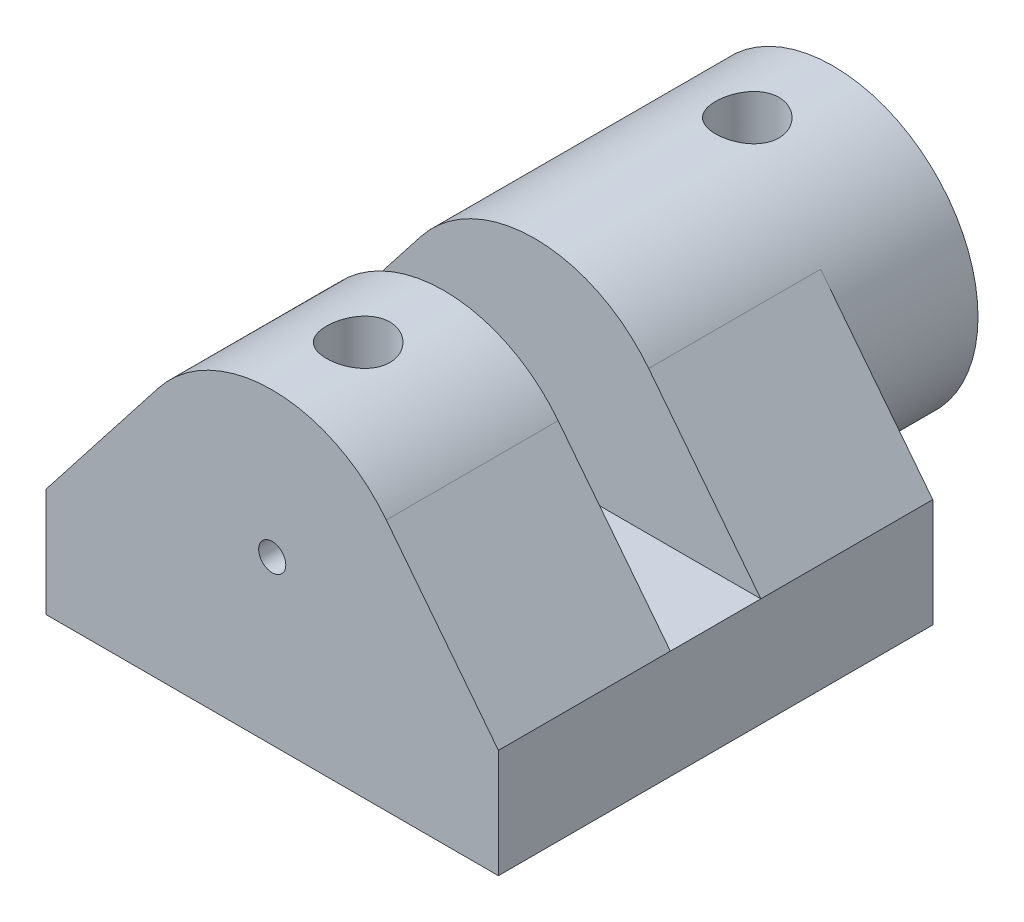
SolidWorks part; units mm, degrees
ref_plane "Front Plane" through (0, 0, 0) normal (0, 0, 1) x (1, 0, 0)
ref_plane "Top Plane" through (0, 0, 0) normal (0, 1, 0) x (1, 0, 0)
ref_plane "Right Plane" through (0, 0, 0) normal (1, 0, 0) x (0, 0, -1)
sketch "Sketch1" plane through (0, 0, 0) normal (0, 0, 1) x (1, 0, 0)
  line L0 (-12.5, 0) -> (12.5, 0)
  line L1 (12.5, 0) -> (12.5, 6)
  line L2 (12.5, 6) -> (6.3025, 13.9273)
  line L3 (-6.3025, 13.9273) -> (-12.5, 6)
  line L4 (-12.5, 6) -> (-12.5, 0)
  arc A0 (6.3025, 13.9273) -> (-6.3025, 13.9273) centre (0, 9) ccw
  circle A1 centre (0, 9) radius 0.75
  point P0 (0, 0)
  dimension "D2" = 8
  dimension "D5" = 1.5
  dimension "D3" = 25
  dimension "D1" = 6
  dimension "D4" = 3
extrude "Boss-Extrude1" add sketch "Sketch1" along normal blind 24
sketch "Sketch2" plane through (0, 0, 0) normal (0, 0, -1) x (-1, 0, 0)
  circle A1 centre (0, 9) radius 2.65
  circle A2 centre (0, 9) radius 8
  arc A3 (6.3025, 13.9273) -> (-6.3025, 13.9273) centre (0, 9) ccw construction
  circle A4 centre (0, 9) radius 0.75 construction
  dimension "D1" = 5.3
extrude "Boss-Extrude2" add sketch "Sketch2" along normal blind 7
sketch "Sketch4" plane through (12.5, 0, 0) normal (1, 0, 0) x (0, 0, -1)
  line L0 (-24, 6) -> (0, 6) construction
  line L1 (-14.5, 6) -> (-9.5, 6)
  line L2 (-14.5, 6) -> (-14.5, 17)
  line L3 (-14.5, 17) -> (-9.5, 17)
  line L4 (-9.5, 6) -> (-9.5, 17)
  line L5 (7, 17) -> (-24, 17) construction
  point P8 (-12, 6)
  point P9 (-12, 6)
  dimension "D1" = 5
extrude "Cut-Extrude1" cut sketch "Sketch4" against normal through all
sketch "Sketch5" plane through (0, 0, 0) normal (0, -1, 0) x (1, 0, 0)
  line L0 (-6.3025, 14.5) -> (6.3025, 14.5) construction
  line L1 (-6.3025, 14.5) -> (6.3025, 14.5) construction
  line L2 (0, 14.5) -> (0, 24) construction
  line L3 (-12.5, 24) -> (12.5, 24) construction
  circle A0 centre (0, 19.25) radius 1.75
  point P6 (0, 19.25)
  dimension "D1" = 3.5
extrude "Cut-Extrude2" cut sketch "Sketch5" against normal through all
ref_plane "Plane1" through (0, 9, 0) normal (0, -1, 0) x (-1, 0, 0)
sketch "Sketch6" plane through (0, 9, 0) normal (0, -1, 0) x (-1, 0, 0)
  line L0 (0, 7) -> (0, 0) construction
  line L1 (0, 7) -> (0, 0) construction
  line L2 (2.65, 7) -> (-2.65, 7) construction
  circle A0 centre (0, 2.25) radius 1.75
  dimension "D1" = 3.5
  dimension "D2" = 3
extrude "Cut-Extrude3" cut sketch "Sketch6" against normal through all
